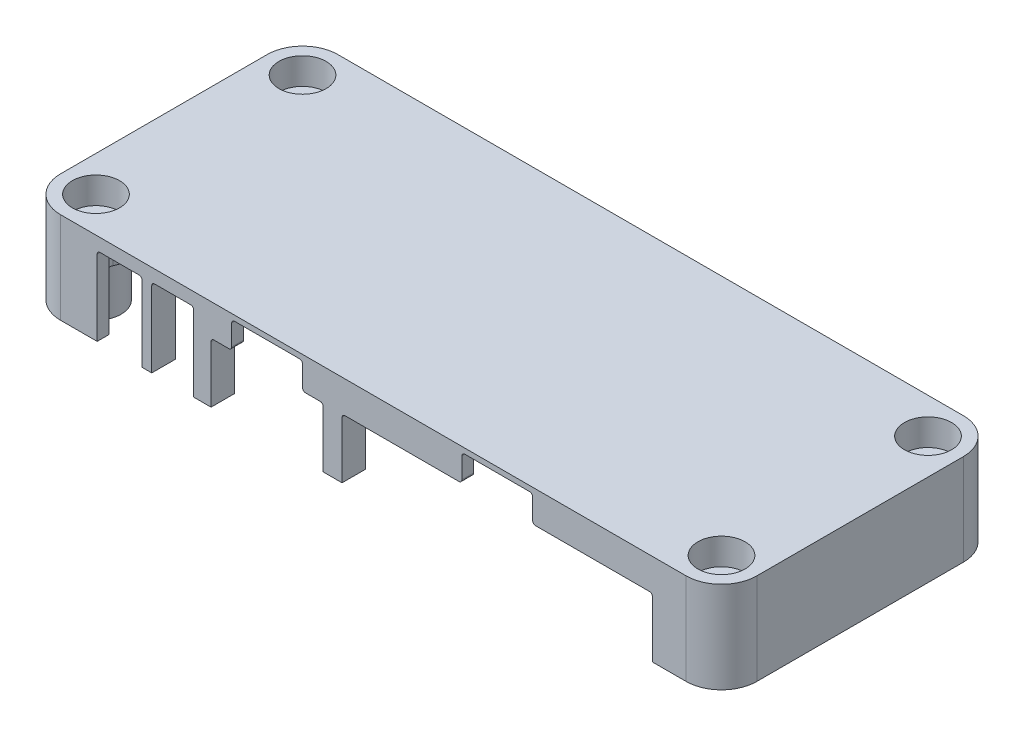
SolidWorks part; units mm, degrees
ref_plane "Front Plane" through (0, 0, 0) normal (0, 0, 1) x (1, 0, 0)
ref_plane "Top Plane" through (0, 0, 0) normal (0, 1, 0) x (1, 0, 0)
ref_plane "Right Plane" through (0, 0, 0) normal (1, 0, 0) x (0, 0, -1)
sketch "Sketch1" plane through (0, 0, 0) normal (0, 1, 0) x (1, 0, 0)
  line L5 (-59, -23.5) -> (59, -23.5)
  line L6 (-59, -23.5) -> (-59, 23.5)
  line L7 (-59, 23.5) -> (59, 23.5)
  line L8 (59, -23.5) -> (59, 23.5)
  line L9 (-59, -23.5) -> (59, 23.5) construction
  line L10 (-59, 23.5) -> (59, -23.5) construction
  point P0 (0, 0)
  dimension "D1" = 47
  dimension "D2" = 118
extrude "Boss-Extrude1" add sketch "Sketch1" along normal blind 15.5
fillet "Fillet1" radius 6 4 edges at (-59, 7.75, -23.5) (59, 7.75, -23.5) (59, 7.75, 23.5) (-59, 7.75, 23.5)
sketch "Sketch4" plane through (0, 15.5, 0) normal (0, 1, 0) x (1, 0, 0)
  line L0 (0, -55) -> (0, 55) construction
  line L1 (-55, 0) -> (55, 0) construction
  circle A0 centre (53, -17.5) radius 2.25
  arc A1 (53, -23.5) -> (59, -17.5) centre (53, -17.5) ccw construction
  circle A2 centre (-53, -17.5) radius 2.25
  circle A3 centre (53, 17.5) radius 2.25
  circle A4 centre (-53, 17.5) radius 2.25
  dimension "D1" = 4.5
extrude "Cut-Extrude1" cut sketch "Sketch4" against normal through all
sketch "Sketch7" plane through (0, 15.5, 0) normal (0, 1, 0) x (1, 0, 0)
  line L0 (-55, 0) -> (55, 0) construction
  line L1 (0, -55) -> (0, 55) construction
  circle A0 centre (53, 17.5) radius 4
  circle A1 centre (53, 17.5) radius 2.25 construction
  circle A2 centre (53, -17.5) radius 4
  circle A3 centre (-53, -17.5) radius 4
  circle A4 centre (-53, 17.5) radius 4
  point P2 (0, 0)
  dimension "D1" = 8
extrude "Cut-Extrude2" cut sketch "Sketch7" against normal blind 4.5
sketch "Sketch6" plane through (0, 15.5, 0) normal (0, 1, 0) x (1, 0, 0)
  line L0 (57, 13.0279) -> (57, -13.0279)
  line L2 (48.5279, 21.5) -> (-48.5279, 21.5)
  line L3 (53, 23.5) -> (-53, 23.5) construction
  line L4 (59, -17.5) -> (59, 17.5) construction
  line L5 (59, 0) -> (-59, 0) construction
  line L6 (-59, 17.5) -> (-59, -17.5) construction
  line L7 (0, 23.5) -> (0, -23.5) construction
  line L8 (-53, -23.5) -> (53, -23.5) construction
  line L9 (48.5279, -21.5) -> (-48.5279, -21.5)
  line L10 (-57, 13.0279) -> (-57, -13.0279)
  arc A0 (57, 13.0279) -> (48.5279, 21.5) centre (53, 17.5) cw
  arc A1 (59, 17.5) -> (53, 23.5) centre (53, 17.5) ccw construction
  arc A2 (57, -13.0279) -> (48.5279, -21.5) centre (53, -17.5) ccw
  arc A3 (-57, -13.0279) -> (-48.5279, -21.5) centre (-53, -17.5) cw
  arc A4 (-57, 13.0279) -> (-48.5279, 21.5) centre (-53, 17.5) ccw
  point P26 (57, 0)
  point P30 (0, -21.5)
  point P35 (0, 21.5)
  dimension "D1" = 2
  dimension "D2" = 2
extrude "Cut-Extrude3" cut sketch "Sketch6" along normal offset from surface (13.5 mm away) 2 from surface at -15.5 up to face at (-53, 15.5, -21.5) starting at face at (-53, 0, 15.25)
sketch "Sketch8" plane through (0, 0, 0) normal (0, -1, 0) x (1, 0, 0)
  line L0 (48.5279, -21.5) -> (51.5639, -21.5)
  line L1 (57, -13.0279) -> (57, -16.0639)
  line L2 (55, 0) -> (-55, 0) construction
  line L3 (48.5279, 21.5) -> (51.5639, 21.5)
  line L4 (57, 13.0279) -> (57, 16.0639)
  line L5 (0, -55) -> (0, 55) construction
  line L6 (-48.5279, -21.5) -> (-51.5639, -21.5)
  line L7 (-57, -13.0279) -> (-57, -16.0639)
  line L8 (-57, 13.0279) -> (-57, 16.0639)
  line L9 (-48.5279, 21.5) -> (-51.5639, 21.5)
  arc A0 (51.5639, -21.5) -> (57, -16.0639) centre (53, -17.5) cw
  circle A1 centre (53, -17.5) radius 2.25 construction
  arc A2 (48.5279, -21.5) -> (57, -13.0279) centre (53, -17.5) cw
  arc A3 (57, -13.0279) -> (48.5279, -21.5) centre (53, -17.5) ccw construction
  arc A4 (51.5639, 21.5) -> (57, 16.0639) centre (53, 17.5) ccw
  arc A5 (48.5279, 21.5) -> (57, 13.0279) centre (53, 17.5) ccw
  arc A6 (-48.5279, -21.5) -> (-57, -13.0279) centre (-53, -17.5) ccw
  arc A7 (-51.5639, -21.5) -> (-57, -16.0639) centre (-53, -17.5) ccw
  arc A8 (-51.5639, 21.5) -> (-57, 16.0639) centre (-53, 17.5) cw
  arc A9 (-48.5279, 21.5) -> (-57, 13.0279) centre (-53, 17.5) cw
  point P21 (50.0459, 21.5)
  point P31 (-50.0459, 21.5)
  arc M14 (48.5279, 21.5) -> (57, 13.0279) centre (53, 17.5) ccw
  arc M16 (57, -13.0279) -> (48.5279, -21.5) centre (53, -17.5) ccw
  arc M18 (-48.5279, -21.5) -> (-57, -13.0279) centre (-53, -17.5) ccw
  arc M20 (-57, 13.0279) -> (-48.5279, 21.5) centre (-53, 17.5) ccw
  dimension "D1" = 2
extrude "Cut-Extrude4" cut sketch "Sketch8" along direction (0, -1, 0) on the side against the normal offset from surface (9 mm away) 2 contours L0 A0 L1 M16 | A4 L3 L4 M14 | L9 A8 L8 M20 | A7 L6 L7 M18
fillet "Fillet2" radius 1 16 edges at (-51.5639, 4.5, 21.5) (-57, 4.5, 16.0639) (-48.5279, 11.25, 21.5) (-57, 11.25, 13.0279) (-57, 11.25, -13.0279) (-48.5279, 11.25, -21.5) (-57, 4.5, -16.0639) (-51.5639, 4.5, -21.5) (57, 4.5, 16.0639) (51.5639, 4.5, 21.5) (57, 11.25, 13.0279) (48.5279, 11.25, 21.5) (48.5279, 11.25, -21.5) (57, 11.25, -13.0279) (51.5639, 4.5, -21.5) (57, 4.5, -16.0639)
sketch "Sketch9" plane through (0, 0, 23.5) normal (0, 0, 1) x (1, 0, 0)
  line L0 (-53, 0) -> (53, 0) construction
  line L1 (-46.8, 0) -> (-39.2, 0)
  line L2 (-46.8, 0) -> (-46.8, 13.3)
  line L3 (-46.8, 13.3) -> (-39.2, 13.3)
  line L4 (47.3, 0) -> (47.3, 10.1)
  line L5 (0, 0) -> (0, 15.5) construction
  line L6 (-53, 15.5) -> (53, 15.5) construction
  line L7 (-59, 0) -> (-59, 15.5) construction
  line L8 (59, 15.5) -> (59, 0) construction
  line L9 (-30.45, 13.3) -> (-30.45, 0)
  line L10 (-27.5, 10.1) -> (-27.5, 0)
  line L11 (-27.5, 10.1) -> (-24, 10.1)
  line L12 (-8.5, 10.1) -> (-8.5, 0)
  line L13 (-5.3, 10.1) -> (-5.3, 0)
  line L14 (-5.3, 10.1) -> (15, 10.1)
  line L15 (-8.5, 10.1) -> (-5.3, 10.1) construction
  line L16 (-39.2, 13.3) -> (-39.2, 0)
  line L17 (-37.55, 13.3) -> (-37.55, 0)
  line L18 (-37.55, 13.3) -> (-30.45, 13.3)
  line L19 (-37.55, 0) -> (-30.45, 0)
  line L20 (-27.5, 0) -> (-8.5, 0)
  line L21 (-5.3, 0) -> (47.3, 0)
  line L22 (-24, 10.1) -> (-24, 14.6)
  line L23 (-24, 14.6) -> (-12, 14.6)
  line L24 (-12, 14.6) -> (-12, 10.1)
  line L25 (-18, 0) -> (-18, 15.5) construction
  line L26 (-12, 10.1) -> (-8.5, 10.1)
  line L27 (21, 0) -> (21, 15.5) construction
  line L28 (15, 10.1) -> (15, 14.6)
  line L29 (15, 14.6) -> (27, 14.6)
  line L30 (27, 14.6) -> (27, 10.1)
  line L31 (27, 10.1) -> (47.3, 10.1)
  dimension "D1" = 2.2
  dimension "D2" = 12.2
  dimension "D3" = 11.7
  dimension "D4" = 5.4
  dimension "D5" = 7.6
  dimension "D6" = 1.65
  dimension "D7" = 2.95
  dimension "D8" = 7.1
  dimension "D9" = 3.2
  dimension "D10" = 19
  dimension "D11" = 4.5
  dimension "D12" = 12
  dimension "D13" = 12
extrude "Cut-Extrude5" cut sketch "Sketch9" against normal blind 7
sketch "Sketch10" plane through (0, 0, -23.5) normal (0, 0, -1) x (-1, 0, 0)
  line L0 (-53, 0) -> (53, 0) construction
  line L1 (-47.55, 0) -> (47.55, 0)
  line L2 (-47.55, 0) -> (-47.55, 13.5)
  line L3 (-47.55, 13.5) -> (47.55, 13.5)
  line L4 (47.55, 0) -> (47.55, 13.5)
  line L5 (0, 15.5) -> (0, 0) construction
  line L7 (-53, 15.5) -> (53, 15.5) construction
  dimension "D1" = 2
  dimension "D2" = 95.1
extrude "Cut-Extrude6" cut sketch "Sketch10" against normal blind 20
sketch "Sketch14" plane through (0, 0, 16.5) normal (0, 0, 1) x (1, 0, 0)
  line L4 (47.0839, 9) -> (47.3, 9)
  line L5 (47.3, 9) -> (47.3, 10.1)
  line L6 (47.3, 10.1) -> (47.0839, 10.1)
  line L7 (47.0839, 10.1) -> (47.0839, 9)
  line L8 (47.0839, 9) -> (47.3, 9)
  line L9 (47.3, 9) -> (47.3, 10.1)
  line L10 (47.3, 10.1) -> (47.0839, 10.1)
  line L11 (47.0839, 10.1) -> (47.0839, 9)
  dimension "D1" = 0
extrude "Cut-Extrude7" cut sketch "Sketch14" against normal up to next
fillet "Fillet4" radius 0.5 11 edges at (-47.579, 11.25, -20.0714) (47.579, 11.25, -20.0714) (47.3, 9.55, 21.281) (47.3, 9.55, 19.3735) (47.55, 11.25, -20.9849) (-47.55, 11.25, -20.9849) (-47.55, 11.25, -20.0095) (-47.55, 11.25, -14.9905) (47.55, 11.25, -14.9905) (47.55, 11.25, -20.0095) (47.3, 9.55, 15.6265)
sketch "Sketch15" plane through (0, 0, 21.5) normal (0, 0, -1) x (-1, 0, 0)
  line L0 (12, 13.5) -> (-15, 13.5) construction
  line L1 (8.5, 0) -> (5.3, 0)
  line L2 (8.5, 0) -> (8.5, 13.5)
  line L3 (8.5, 13.5) -> (5.3, 13.5)
  line L4 (5.3, 0) -> (5.3, 13.5)
  line L5 (5.3, 10.1) -> (5.3, 0) construction
  line L6 (46.6754, 13.5) -> (24, 13.5) construction
  line L7 (39.2, 0) -> (37.55, 0)
  line L8 (39.2, 0) -> (39.2, 13.5)
  line L9 (39.2, 13.5) -> (37.55, 13.5)
  line L10 (37.55, 0) -> (37.55, 13.5)
  line L11 (37.55, 13.3) -> (37.55, 0) construction
  line L12 (27.5, 10.1) -> (27.5, 0) construction
  line L13 (30.45, 0) -> (27.5, 0)
  line L14 (30.45, 0) -> (30.45, 13.5)
  line L15 (30.45, 13.5) -> (27.5, 13.5)
  line L16 (27.5, 0) -> (27.5, 13.5)
extrude "Boss-Extrude2" add sketch "Sketch15" along normal blind 2
fillet "Fillet11" radius 0.5 29 edges at (-24, 13.5, 19) (-18, 13.5, 16.5) (47.3323, 10.1, 21.3158) (-12, 10.1, 22.5) (-46.8, 13.3, 22.4961) (-39.2, 13.3, 22.5) (-37.55, 13.3, 22.5) (-27.5, 10.1, 22.5) (-24, 10.1, 22.5) (-30.45, 13.3, 22.5) (-24, 14.05, 16.5) (-24, 14.6, 20) (-18, 14.6, 16.5) (-12, 14.05, 16.5) (-12, 13.5, 19) (-12, 14.6, 20) (-8.5, 10.1, 22.5) (-5.3, 10.1, 22.5) (15, 10.1, 22.5) (15, 13.5, 19) (15, 14.05, 16.5) (15, 14.6, 20) (27, 14.05, 16.5) (21, 14.6, 16.5) (21, 13.5, 16.5) (27, 13.5, 19) (27, 10.1, 22.5) (27, 14.6, 20) (47.3, 10.1, 22.4963)
